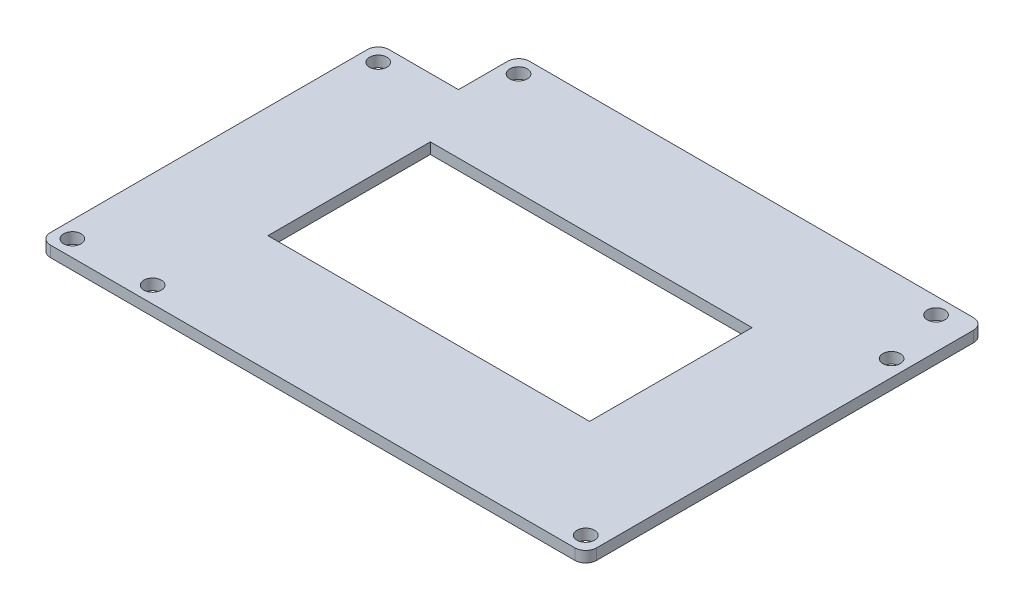
SolidWorks part; units mm, degrees
ref_plane "前视基准面" through (0, 0, 0) normal (0, 0, 1) x (1, 0, 0)
ref_plane "上视基准面" through (0, 0, 0) normal (0, 1, 0) x (1, 0, 0)
ref_plane "右视基准面" through (0, 0, 0) normal (1, 0, 0) x (0, 0, -1)
other "Configuration Table"
sketch "草图1" plane through (0, 0, 0) normal (0, 1, 0) x (1, 0, 0)
  line L0 (0, 31) -> (0, -31) construction
  line L1 (48, -31) -> (-48, -31)
  line L2 (50, -29) -> (50, 29)
  line L3 (48, 31) -> (-48, 31)
  line L4 (-50, -29) -> (-50, 29)
  line L5 (50, -31) -> (-50, 31) construction
  line L6 (50, 31) -> (-50, -31) construction
  line L7 (-50, 0) -> (50, 0) construction
  line L8 (7.35, 42) -> (7.35, -31) construction
  line L9 (-35.3, -31) -> (50, -31)
  line L10 (-35.3, -31) -> (-35.3, 40)
  line L11 (-33.3, 42) -> (48, 42)
  line L12 (50, -31) -> (50, 40)
  line L13 (7.35, 5.5) -> (50, 5.5) construction
  circle A0 centre (-47, 28) radius 1.6
  circle A1 centre (-47, -28) radius 1.6
  circle A2 centre (47, -28) radius 1.6
  circle A3 centre (47, 28) radius 1.6
  arc A4 (-48, -31) -> (-50, -29) centre (-48, -29) cw
  arc A5 (48, -31) -> (50, -29) centre (48, -29) ccw
  arc A6 (50, 29) -> (48, 31) centre (48, 29) ccw
  arc A7 (-48, 31) -> (-50, 29) centre (-48, 29) ccw
  circle A8 centre (-32.3, -28) radius 1.6
  circle A9 centre (-32.3, 39) radius 1.6
  circle A10 centre (44.1445, 39) radius 1.6
  arc A11 (48, 42) -> (50, 40) centre (48, 40) cw
  arc A12 (-35.3, 40) -> (-33.3, 42) centre (-33.3, 40) cw
  point P0 (0, 0)
  point P45 (50, 42)
  point P48 (-35.3, 42)
  dimension "D5" = 3.2
  dimension "D6" = 2
  dimension "D10" = 3.2
  dimension "D11" = 2
  dimension "D1" = 62
  dimension "D2" = 100
  dimension "D3" = 94
  dimension "D4" = 56
  dimension "D7" = 85.3
  dimension "D8" = 73
  dimension "D9" = 67
extrude "凸台-拉伸1" add sketch "草图1" along normal blind 2 contours L2 A6 L3 L10 L1 A5 A8 A3 A2 | L3 A7 L4 A4 L1 L10 A0 A1 | A12 L10 L3 A6 L12 A11 L11 A10 A9
sketch "草图2" plane through (0, 2, 0) normal (0, 1, 0) x (1, 0, 0)
  line L1 (-29.5925, 20.1422) -> (29.3097, 20.1422)
  line L2 (-29.5925, 20.1422) -> (-29.5925, -9.6034)
  line L3 (-29.5925, -9.6034) -> (29.3097, -9.6034)
  line L4 (29.3097, 20.1422) -> (29.3097, -9.6034)
extrude "切除-拉伸1" cut sketch "草图2" against normal up to next
